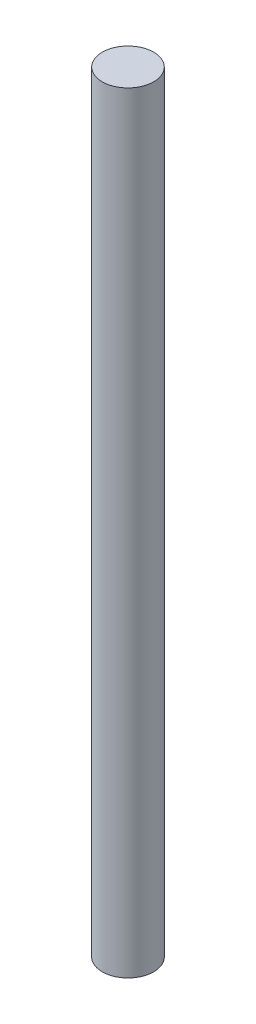
SolidWorks part; units mm, degrees
ref_plane "Ön Düzlem" through (0, 0, 0) normal (0, 0, 1) x (1, 0, 0)
ref_plane "Üst Düzlem" through (0, 0, 0) normal (0, 1, 0) x (1, 0, 0)
ref_plane "Sağ Düzlem" through (0, 0, 0) normal (1, 0, 0) x (0, 0, -1)
sketch "Çizim2" plane through (0, 0, 0) normal (0, 1, 0) x (1, 0, 0)
  circle A0 centre (0, 0) radius 5
  dimension "D1" = 10
extrude "Yükseklik-Ekstrüzyon1" add sketch "Çizim2" along normal blind 150
